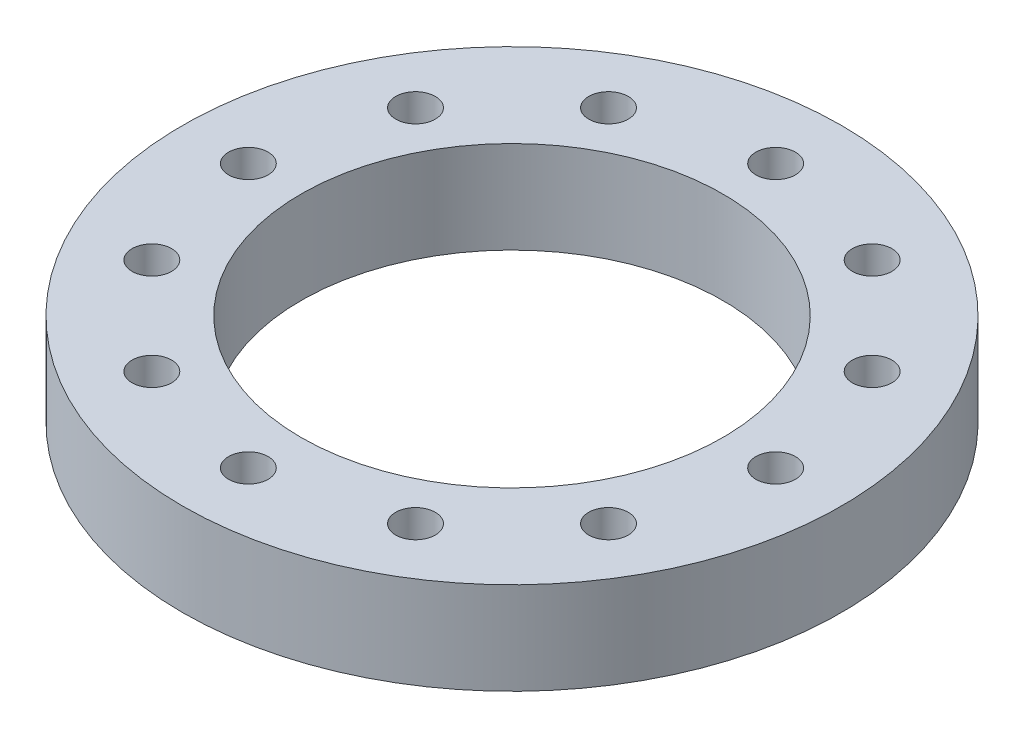
SolidWorks part; units mm, degrees
ref_plane "前视基准面" through (0, 0, 0) normal (0, 0, 1) x (1, 0, 0)
ref_plane "上视基准面" through (0, 0, 0) normal (0, 1, 0) x (1, 0, 0)
ref_plane "右视基准面" through (0, 0, 0) normal (1, 0, 0) x (0, 0, -1)
other "Configuration Table"
sketch "草图1" plane through (0, 0, 0) normal (0, 1, 0) x (1, 0, 0)
  circle A0 centre (0, 0) radius 16
  circle A1 centre (0, 0) radius 25
  circle A3 centre (0, 20) radius 1.5
  circle A4 centre (10, 17.3205) radius 1.5
  circle A5 centre (17.3205, 10) radius 1.5
  circle A6 centre (20, 0) radius 1.5
  circle A7 centre (17.3205, -10) radius 1.5
  circle A8 centre (10, -17.3205) radius 1.5
  circle A9 centre (0, -20) radius 1.5
  circle A10 centre (-10, -17.3205) radius 1.5
  circle A11 centre (-17.3205, -10) radius 1.5
  circle A12 centre (-20, 0) radius 1.5
  circle A13 centre (-17.3205, 10) radius 1.5
  circle A14 centre (-10, 17.3205) radius 1.5
  dimension "D1" = 32
  dimension "D2" = 50
  dimension "D4" = 3
  dimension "D5" = 12
extrude "凸台-拉伸1" add sketch "草图1" along normal blind 7
